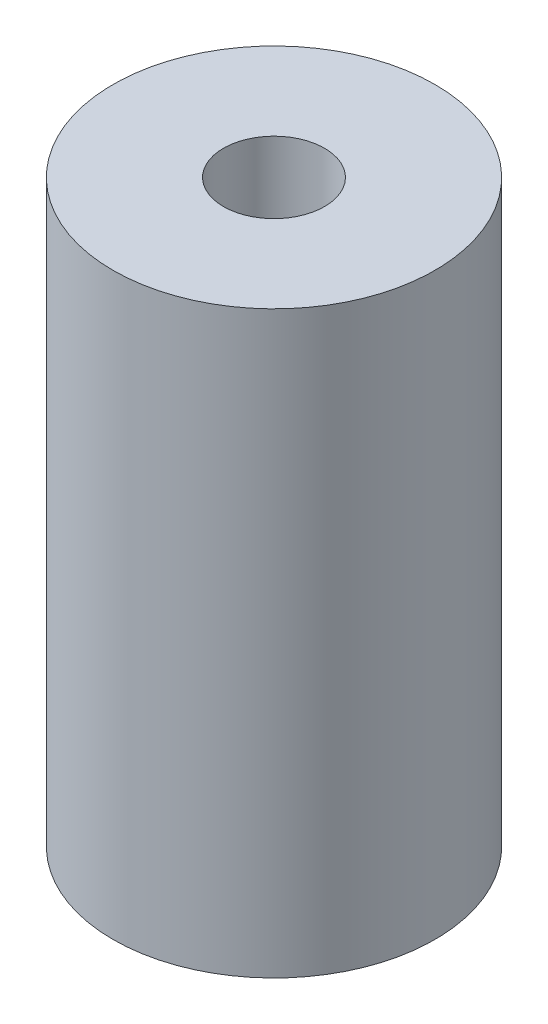
SolidWorks part; units mm, degrees
ref_plane "Front Plane" through (0, 0, 0) normal (0, 0, 1) x (1, 0, 0)
ref_plane "Top Plane" through (0, 0, 0) normal (0, 1, 0) x (1, 0, 0)
ref_plane "Right Plane" through (0, 0, 0) normal (1, 0, 0) x (0, 0, -1)
sketch "Sketch1" plane through (0, 0, 0) normal (0, 1, 0) x (1, 0, 0)
  circle A0 centre (0, 0) radius 3.175
  dimension "D1" = 6.35
extrude "Boss-Extrude1" add sketch "Sketch1" along normal blind 11.43
hole_wizard "#3-48 Tapped Hole1" positions "Sketch3" profile "Sketch2" tap size "#3-48" standard "ANSI Inch" end condition through all
sketch "Sketch3" plane through (0, 11.43, 0) normal (0, 1, 0) x (1, 0, 0)
  point P0 (0, 0)
sketch "Sketch2" plane through (0, 11.43, 0) normal (1, 0, 0) x (0, 0, 1)
  line L0 (0, 0) -> (0, 11.43)
  line L1 (0, 11.43) -> (0.9969, 11.43)
  line L2 (0.9969, 11.43) -> (0.9969, 0)
  line L5 (0.9969, 0) -> (0, 0)
  line L11 (0, -6.35) -> (0, 107.95) construction
  dimension "Thread Major Dia." = 1.9939
  dimension "Thru Tap Drill Depth" = 11.43
